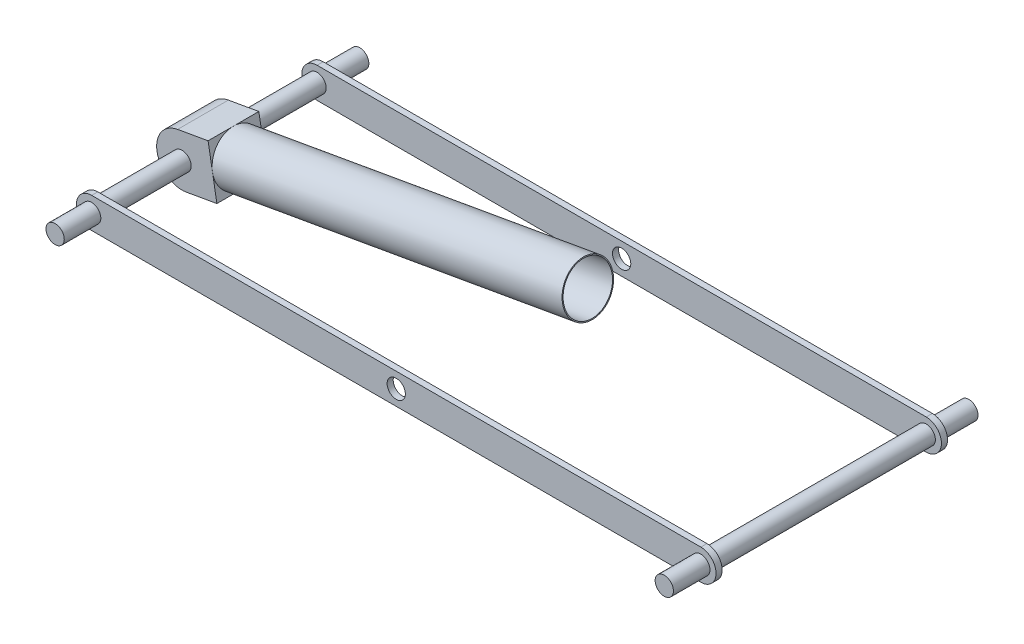
SolidWorks part; units mm, degrees
ref_plane "前视" through (0, 0, 0) normal (0, 0, 1) x (1, 0, 0)
ref_plane "上视" through (0, 0, 0) normal (0, 1, 0) x (1, 0, 0)
ref_plane "右视" through (0, 0, 0) normal (1, 0, 0) x (0, 0, -1)
sketch "草图1" plane through (0, 0, 0) normal (0, 0, 1) x (1, 0, 0)
  line L0 (0, 30.3262) -> (0, -38.9861) construction
  line L1 (-43.5575, 0) -> (50.3438, 0) construction
  circle A0 centre (0, 0) radius 15
  circle A1 centre (1000, 0) radius 15
  dimension "D1" = 30
  dimension "D3" = 1000
  dimension "D2" = 2
extrude "凸台-拉伸1" add sketch "草图1" along normal mid plane 500
ref_plane "基准面1" through (0, 0, 180) normal (0, 0, 1) x (1, 0, 0)
sketch "草图2" plane through (0, 0, 180) normal (0, 0, 1) x (1, 0, 0)
  line L0 (0, 25) -> (1000, 25)
  line L1 (1000, -25) -> (0, -25)
  arc A0 (0, 25) -> (0, -25) centre (0, 0) ccw
  arc A1 (1000, -25) -> (1000, 25) centre (1000, 0) ccw
  dimension "D1" = 50
  dimension "D2" = 50
extrude "凸台-拉伸2" add sketch "草图2" along normal blind 10 separate body
mirror "镜向2" about plane through (0, 0, 0) normal (0, 0, 1) of bodies 103
sketch "草图3" plane through (0, 0, 0) normal (0, 0, 1) x (1, 0, 0)
  circle A0 centre (500, 0) radius 15
  dimension "D1" = 30
  dimension "D2" = 500
extrude "切除-拉伸1" cut sketch "草图3" against normal mid plane 500
sketch "草图4" plane through (0, 0, 0) normal (0, 0, 1) x (1, 0, 0)
  line L0 (-4.3412, 24.6202) -> (25.6588, 29.91)
  line L1 (4.3412, -24.6202) -> (34.3412, -19.3304)
  line L2 (25.6588, 29.91) -> (34.3412, -19.3304)
  line L3 (-63.7871, 0) -> (131.2223, 0) construction
  arc A0 (-4.3412, 24.6202) -> (4.3412, -24.6202) centre (0, 0) ccw
  dimension "D1" = 30
  dimension "D2" = 30
  dimension "D3" = 10
extrude "凸台-拉伸3" add sketch "草图4" along normal mid plane 50 separate body
sketch "草图5" plane through (30, 5.2898, 0) normal (0.9848, 0.1736, 0) x (0, 0, -1)
  line L0 (-25, 25) -> (25, 25) construction
  circle A0 centre (0, 0) radius 25
  circle A1 centre (0, 0) radius 24
  dimension "D1" = 1
extrude "凸台-拉伸4" add sketch "草图5" along normal blind 350 separate body
scale "缩放比例1" bodies to scale 102 106 101 105 scale about origin uniform scaling yes scale factor 0.6
